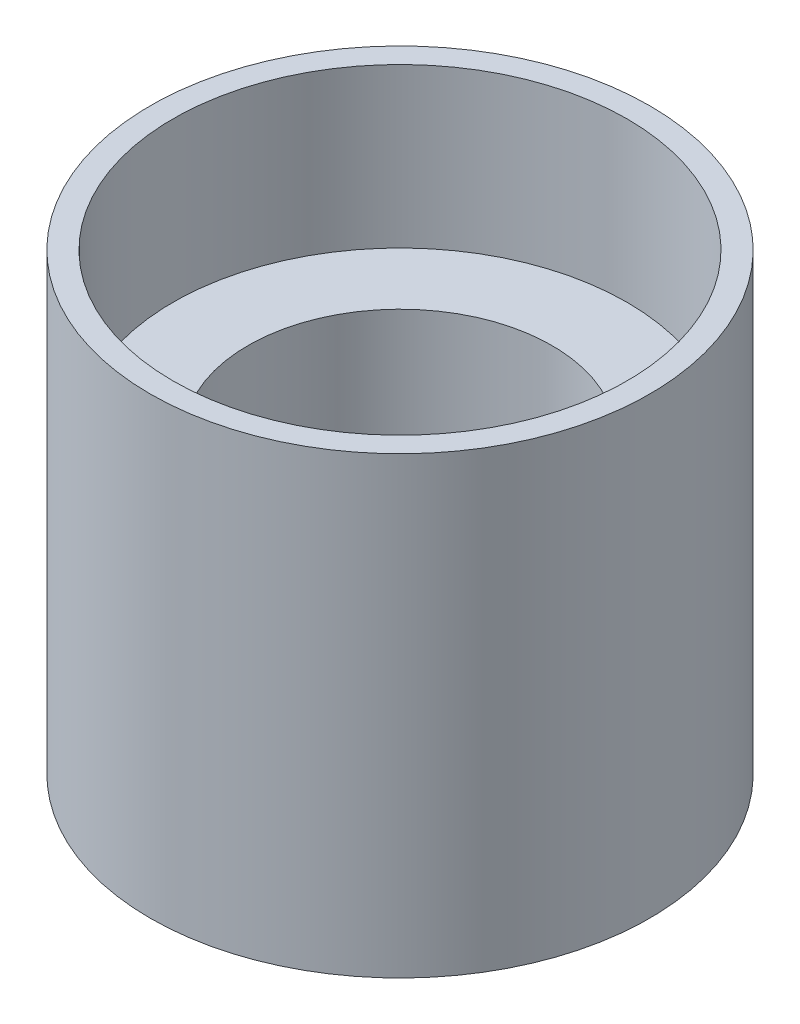
SolidWorks part; units mm, degrees
ref_plane "Front Plane" through (0, 0, 0) normal (0, 0, 1) x (1, 0, 0)
ref_plane "Top Plane" through (0, 0, 0) normal (0, 1, 0) x (1, 0, 0)
ref_plane "Right Plane" through (0, 0, 0) normal (1, 0, 0) x (0, 0, -1)
sketch "Sketch1" plane through (0, 0, 0) normal (0, 1, 0) x (1, 0, 0)
  circle A0 centre (0, 0) radius 11
  dimension "D1" = 22
extrude "Boss-Extrude1" add sketch "Sketch1" along normal blind 20
sketch "Sketch2" plane through (0, 0, 0) normal (0, 1, 0) x (1, 0, 0)
  circle A0 centre (0, 0) radius 3.25
  dimension "D1" = 6.5
extrude "Cut-Extrude1" cut sketch "Sketch2" along normal blind 20
sketch "Sketch3" plane through (0, 20, 0) normal (0, 1, 0) x (1, 0, 0)
  circle A0 centre (0, 0) radius 6.7
  dimension "D1" = 13.4
extrude "Cut-Extrude2" cut sketch "Sketch3" against normal blind 19
sketch "Sketch5" plane through (0, 20, 0) normal (0, 1, 0) x (1, 0, 0)
  circle A0 centre (0, 0) radius 10
  dimension "D1" = 20
extrude "Cut-Extrude3" cut sketch "Sketch5" against normal blind 7
sketch "Sketch4" plane through (0, 0, 0) normal (1, 0, 0) x (0, 0, -1)
  line L1 (-10, 16.0597) -> (-10, 16.1597)
  line L5 (-10, 16.1597) -> (-9.6457, 16.0597)
  line L6 (0, 0) -> (0, 4.7947) construction
  line L7 (-10, 16.0597) -> (-10, 15.4597)
  line L8 (-10, 20) -> (-10, 13) construction
  line L10 (-9.5, 15.6522) -> (-9.5, 15.8672)
  line L12 (-10, 16.0597) -> (-9.6457, 16.0597) construction
  line L13 (-9.6457, 15.4597) -> (-10, 15.3597)
  line L14 (-10, 15.3597) -> (-10, 15.4597)
  line L15 (-9.6457, 15.4597) -> (-10, 15.4597) construction
  line L16 (-9.6457, 16.0597) -> (-9.6457, 15.4597) construction
  line L17 (-9.5, 15.7597) -> (-9.6462, 15.7597) construction
  line L18 (10, 20) -> (-10, 20) construction
  arc A2 (-9.6457, 15.4597) -> (-9.5, 15.6522) centre (-9.7, 15.6522) ccw
  arc A3 (-9.5, 15.8672) -> (-9.6457, 16.0597) centre (-9.7, 15.8672) ccw
  point P12 (-9.5, 16.0097)
  point P19 (-10, 15.7597)
  dimension "D4" = 0.2
  dimension "D1" = 0.5
  dimension "D2" = 0.6
  dimension "D3" = 4.2403
  dimension "D5" = 0.1
  dimension "D6" = 0.1
revolve "Revolve1" [suppressed] add sketch "Sketch4" angle 360 about L6
